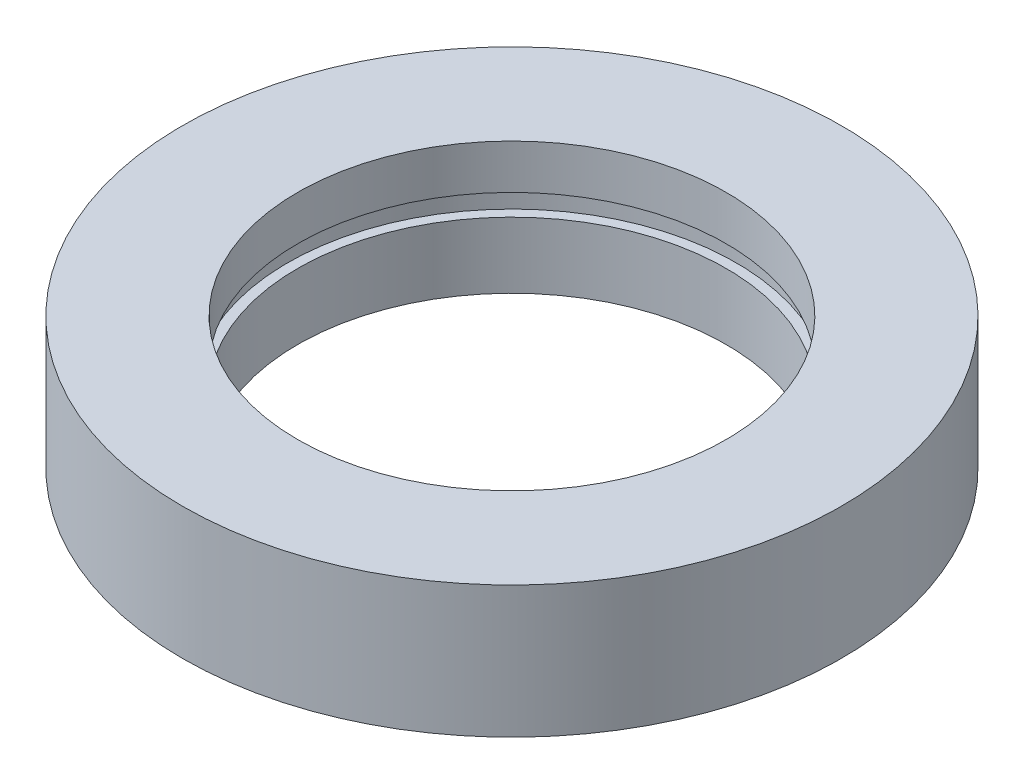
SolidWorks part; units mm, degrees
material "ASTM A36 Steel"
ref_plane "Front Plane" through (0, 0, 0) normal (0, 0, 1) x (1, 0, 0)
ref_plane "Top Plane" through (0, 0, 0) normal (0, 1, 0) x (1, 0, 0)
ref_plane "Right Plane" through (0, 0, 0) normal (1, 0, 0) x (0, 0, -1)
sketch "Sketch1" plane through (0, 0, 0) normal (0, 1, 0) x (1, 0, 0)
  circle A0 centre (0, 0) radius 20
  circle A1 centre (0, 0) radius 13
  dimension "D1" = 40
  dimension "D2" = 26
extrude "Boss-Extrude1" add sketch "Sketch1" along normal blind 8
sketch "Sketch2" plane through (0, 0, 0) normal (1, 0, 0) x (0, 0, -1)
  line L0 (13, 0) -> (13, 8) construction
  line L1 (13, 4) -> (13.6, 4)
  line L2 (13, 4) -> (13, 5.3)
  line L3 (13, 5.3) -> (13.6, 5.3)
  line L4 (13.6, 4) -> (13.6, 5.3)
  line L5 (0, 8) -> (0, -2.0637)
  line L6 (20, 8) -> (-20, 8) construction
  line L7 (-20, 0) -> (20, 0) construction
  dimension "D1" = 1.3
  dimension "D2" = 4
  dimension "D3" = 0.6
revolve "Cut-Revolve1" cut sketch "Sketch2" angle 360 about L5
